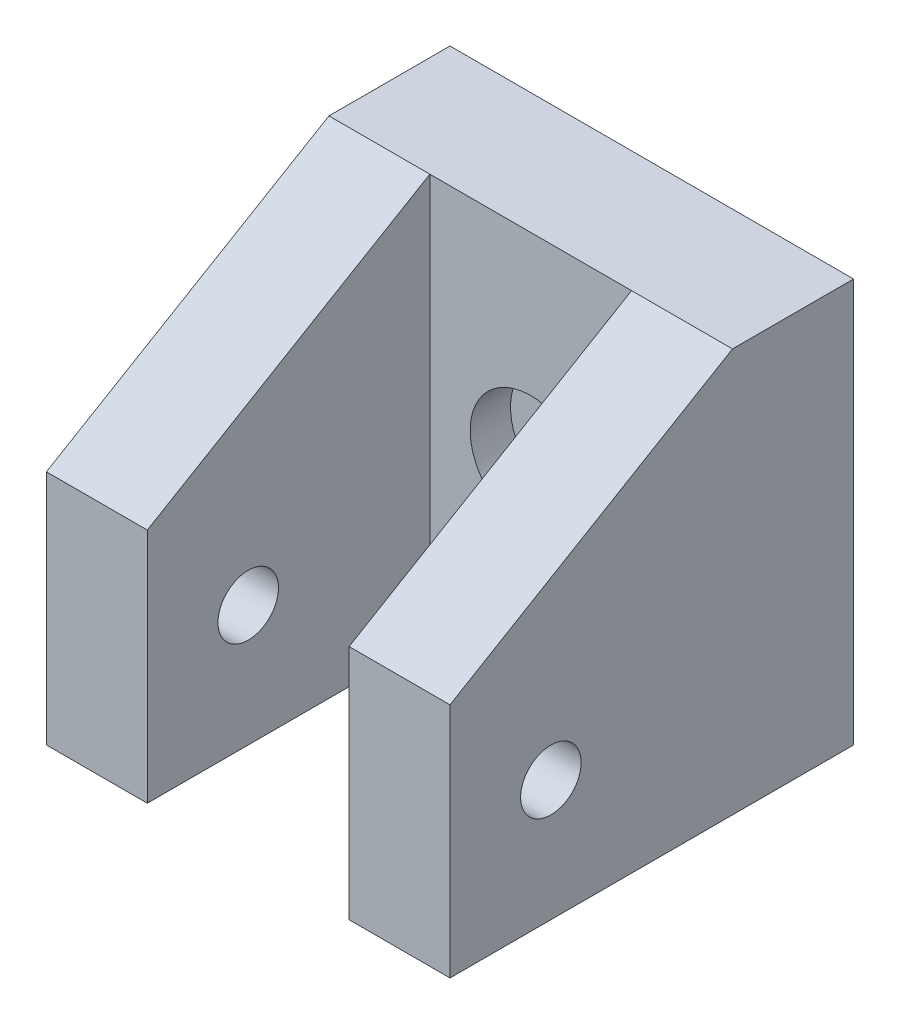
SolidWorks part; units mm, degrees
ref_plane "前视基准面" through (0, 0, 0) normal (0, 0, 1) x (1, 0, 0)
ref_plane "上视基准面" through (0, 0, 0) normal (0, 1, 0) x (1, 0, 0)
ref_plane "右视基准面" through (0, 0, 0) normal (1, 0, 0) x (0, 0, -1)
sketch "草图1" plane through (0, 0, 0) normal (0, 0, 1) x (1, 0, 0)
  line L1 (0, 0) -> (20, 0)
  line L2 (0, 0) -> (0, 20)
  line L3 (0, 20) -> (20, 20)
  line L4 (20, 0) -> (20, 20)
  dimension "D1" = 20
  dimension "D2" = 20
extrude "凸台-拉伸1" add sketch "草图1" along normal blind 20
sketch "草图2" plane through (0, 0, 20) normal (0, 0, 1) x (1, 0, 0)
  line L0 (10, 20) -> (10, 0) construction
  line L1 (20, 20) -> (0, 20) construction
  line L2 (0, 0) -> (20, 0) construction
  line L4 (5, 20) -> (15, 20)
  line L5 (5, 20) -> (5, 0)
  line L6 (5, 0) -> (15, 0)
  line L7 (15, 20) -> (15, 0)
  dimension "D1" = 10
extrude "切除-拉伸1" cut sketch "草图2" against normal blind 14
sketch "草图3" plane through (0, 0, 6) normal (0, 0, 1) x (1, 0, 0)
  line L0 (10, 20) -> (10, 0) construction
  line L1 (15, 20) -> (5, 20) construction
  line L2 (5, 0) -> (15, 0) construction
  line L3 (0, 10.1018) -> (20, 10.1018) construction
  line L4 (0, 20) -> (0, 0) construction
  line L5 (20, 0) -> (20, 20) construction
  circle A0 centre (10, 10) radius 1.6
  dimension "D1" = 3.2
extrude "切除-拉伸2" cut sketch "草图3" against normal through all
sketch "草图5" plane through (0, 0, 6) normal (0, 0, 1) x (1, 0, 0)
  circle A0 centre (10, 10) radius 3
  dimension "D1" = 6
extrude "切除-拉伸3" cut sketch "草图5" against normal blind 2
sketch "草图6" plane through (20, 0, 0) normal (1, 0, 0) x (0, 0, -1)
  line L0 (-20, 10) -> (0, 10) construction
  line L1 (-20, 0) -> (-20, 20) construction
  line L2 (0, 0) -> (0, 20) construction
  line L3 (-20, 20) -> (-6, 20)
  line L4 (-6, 20) -> (-20, 11.7258)
  line L5 (-20, 11.7258) -> (-20, 20)
  circle A0 centre (-15, 6) radius 1.5
  dimension "D1" = 3
  dimension "D2" = 4
  dimension "D3" = 5
extrude "切除-拉伸4" cut sketch "草图6" against normal through all
